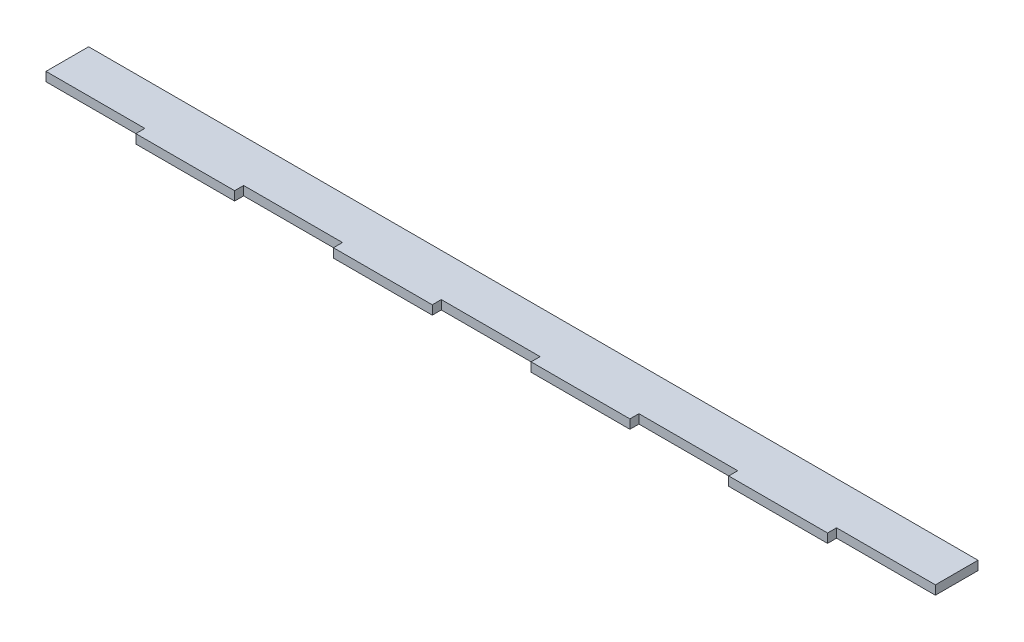
SolidWorks part; units mm, degrees
ref_plane "Front Plane" through (0, 0, 0) normal (0, 0, 1) x (1, 0, 0)
ref_plane "Top Plane" through (0, 0, 0) normal (0, 1, 0) x (1, 0, 0)
ref_plane "Right Plane" through (0, 0, 0) normal (1, 0, 0) x (0, 0, -1)
sketch "Sketch1" plane through (0, 0, 0) normal (0, 1, 0) x (1, 0, 0)
  line L0 (0, 0) -> (34.7778, 0)
  line L2 (0, 0) -> (0, 15)
  line L3 (0, 15) -> (313, 15)
  line L4 (313, 0) -> (313, 15)
  line L5 (34.7778, 0) -> (34.7778, -3.175)
  line L6 (34.7778, -3.175) -> (69.5556, -3.175)
  line L7 (69.5556, -3.175) -> (69.5556, 0)
  line L8 (69.5556, 0) -> (104.3333, 0)
  line L9 (104.3333, 0) -> (104.3333, -3.175)
  line L10 (104.3333, -3.175) -> (139.1111, -3.175)
  line L11 (139.1111, -3.175) -> (139.1111, 0)
  line L12 (139.1111, 0) -> (173.8889, 0)
  line L13 (173.8889, 0) -> (173.8889, -3.175)
  line L14 (173.8889, -3.175) -> (208.6667, -3.175)
  line L15 (208.6667, -3.175) -> (208.6667, 0)
  line L16 (208.6667, 0) -> (243.4444, 0)
  line L17 (243.4444, 0) -> (243.4444, -3.175)
  line L18 (243.4444, -3.175) -> (278.2222, -3.175)
  line L19 (278.2222, -3.175) -> (278.2222, 0)
  line L20 (278.2222, 0) -> (313, 0)
  point P4 (0, 0)
  dimension "D1" = 313
  dimension "D2" = 15
  dimension "D3" = 3.175
extrude "Boss-Extrude1" add sketch "Sketch1" along normal blind 3.175
